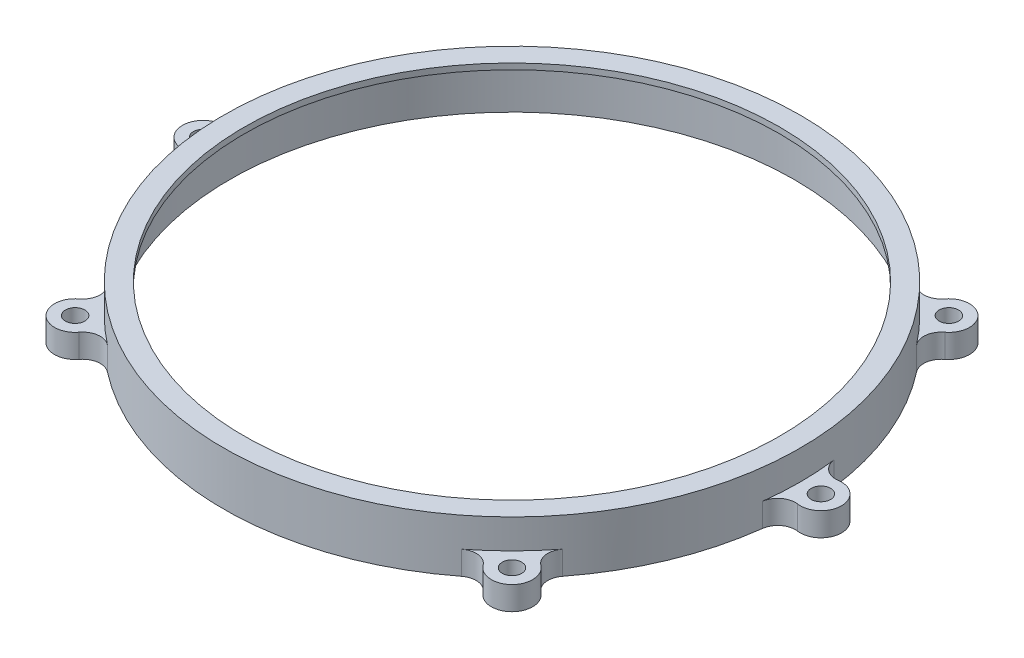
SolidWorks part; units mm, degrees
material "6061 合金"
ref_plane "前视基准面" through (0, 0, 0) normal (0, 0, 1) x (1, 0, 0)
ref_plane "上视基准面" through (0, 0, 0) normal (0, 1, 0) x (1, 0, 0)
ref_plane "右视基准面" through (0, 0, 0) normal (1, 0, 0) x (0, 0, -1)
sketch "草图1" plane through (0, 0, 0) normal (0, 0, 1) x (1, 0, 0)
  line L0 (0, 0) -> (0, 9.3558) construction
  line L1 (48, 8) -> (48, 0)
  line L2 (48, 0) -> (56, 0)
  line L4 (56, 4) -> (49, 4)
  line L5 (49, 4) -> (49, 9)
  line L8 (49, 9) -> (45.5, 9)
  line L9 (45.5, 9) -> (45.5, 8)
  line L10 (45.5, 8) -> (48, 8)
  line L12 (56, 4) -> (56, 0)
  dimension "D1" = 96
  dimension "D2" = 8
  dimension "D3" = 1
  dimension "D4" = 7
  dimension "D5" = 91
  dimension "D6" = 4
  dimension "D8" = 1
revolve "旋转1" add sketch "草图1" angle 360 about L0
hole_wizard "M4 螺纹孔1" positions "草图4" profile "草图3" tap size "M4" standard "GB" end condition through all
sketch "草图4" plane through (0, 0, 0) normal (0, -1, 0) x (-1, 0, 0)
  circle A0 centre (0, 0) radius 52.5 construction
  circle A1 centre (0, 0) radius 56 construction
  point P0 (0, 52.5)
  point P14 (37.1231, 37.1231)
  point P15 (52.5, 0)
  point P16 (37.1231, -37.1231)
  point P17 (0, -52.5)
  point P18 (-37.1231, -37.1231)
  point P19 (-52.5, 0)
  point P20 (-37.1231, 37.1231)
  dimension "D1" = 3.5
  dimension "D2" = 8
cosmetic thread "孔螺蚊线1" parameters "D2"=4
cosmetic thread "孔螺蚊线2" parameters "D2"=4
cosmetic thread "孔螺蚊线3" parameters "D2"=4
cosmetic thread "孔螺蚊线4" parameters "D2"=4
sketch "草图3" plane through (0, 0, -52.5) normal (1, 0, 0) x (0, 0, -1)
  line L0 (0, 0) -> (0, 9)
  line L1 (0, 9) -> (1.65, 9)
  line L2 (1.65, 9) -> (1.65, 0)
  line L5 (1.65, 0) -> (0, 0)
  line L11 (0, -6.35) -> (0, 107.95) construction
  dimension "通孔螺纹孔钻头直径" = 3.3
  dimension "通孔螺纹孔钻头深度" = 9
cosmetic thread "孔螺蚊线5" parameters "D2"=4
cosmetic thread "孔螺蚊线6" parameters "D2"=4
cosmetic thread "孔螺蚊线7" parameters "D2"=4
cosmetic thread "孔螺蚊线8" parameters "D2"=4
sketch "草图5" plane through (0, 0, 0) normal (0, 1, 0) x (1, 0, 0)
  line L0 (-4.95, 0) -> (4.95, 0) construction
  arc A0 (-34.3294, 39.2315) -> (-39.2315, 34.3294) centre (-37.1231, 37.1231) ccw
  circle A1 centre (0, 0) radius 56 construction
  arc A2 (-38.671, 30.0924) -> (-48.6231, 6.066) centre (0, 0) ccw
  arc A3 (34.3294, -39.2315) -> (39.2315, -34.3294) centre (37.1231, -37.1231) ccw
  arc A4 (-38.671, 30.0924) -> (-39.2315, 34.3294) centre (-41.0386, 31.9348) ccw
  arc A5 (-30.0924, 38.671) -> (-34.3294, 39.2315) centre (-31.9348, 41.0386) cw
  arc A6 (3.4663, 52.0154) -> (-3.4663, 52.0154) centre (0, 52.5) ccw construction
  arc A7 (-6.066, 48.6231) -> (-30.0924, 38.671) centre (0, 0) ccw
  arc A8 (-6.066, 48.6231) -> (-3.4663, 52.0154) centre (-6.4374, 51.6) ccw construction
  arc A9 (6.066, 48.6231) -> (3.4663, 52.0154) centre (6.4374, 51.6) cw construction
  arc A10 (39.2315, 34.3294) -> (34.3294, 39.2315) centre (37.1231, 37.1231) ccw
  arc A11 (30.0924, 38.671) -> (6.066, 48.6231) centre (0, 0) ccw
  arc A12 (30.0924, 38.671) -> (34.3294, 39.2315) centre (31.9348, 41.0386) ccw
  arc A13 (38.671, 30.0924) -> (39.2315, 34.3294) centre (41.0386, 31.9348) cw
  arc A14 (52.0154, -3.4663) -> (52.0154, 3.4663) centre (52.5, 0) ccw
  arc A15 (48.6231, 6.066) -> (38.671, 30.0924) centre (0, 0) ccw
  arc A16 (48.6231, 6.066) -> (52.0154, 3.4663) centre (51.6, 6.4374) ccw
  arc A17 (48.6231, -6.066) -> (52.0154, -3.4663) centre (51.6, -6.4374) cw
  circle A18 centre (0, 0) radius 49 construction
  arc A19 (38.671, -30.0924) -> (48.6231, -6.066) centre (0, 0) ccw
  arc A20 (38.671, -30.0924) -> (39.2315, -34.3294) centre (41.0386, -31.9348) ccw
  arc A21 (30.0924, -38.671) -> (34.3294, -39.2315) centre (31.9348, -41.0386) cw
  arc A22 (-3.4663, -52.0154) -> (3.4663, -52.0154) centre (0, -52.5) ccw construction
  arc A23 (6.066, -48.6231) -> (30.0924, -38.671) centre (0, 0) ccw
  arc A24 (6.066, -48.6231) -> (3.4663, -52.0154) centre (6.4374, -51.6) ccw construction
  arc A25 (-6.066, -48.6231) -> (-3.4663, -52.0154) centre (-6.4374, -51.6) cw construction
  arc A26 (-39.2315, -34.3294) -> (-34.3294, -39.2315) centre (-37.1231, -37.1231) ccw
  arc A27 (-30.0924, -38.671) -> (-6.066, -48.6231) centre (0, 0) ccw
  arc A28 (-30.0924, -38.671) -> (-34.3294, -39.2315) centre (-31.9348, -41.0386) ccw
  arc A29 (-38.671, -30.0924) -> (-39.2315, -34.3294) centre (-41.0386, -31.9348) cw
  arc A30 (-52.0154, 3.4663) -> (-52.0154, -3.4663) centre (-52.5, 0) ccw
  arc A31 (-48.6231, -6.066) -> (-38.671, -30.0924) centre (0, 0) ccw
  arc A32 (-48.6231, -6.066) -> (-52.0154, -3.4663) centre (-51.6, -6.4374) ccw
  arc A33 (-48.6231, 6.066) -> (-52.0154, 3.4663) centre (-51.6, 6.4374) cw
  arc A34 (-6.066, 48.6231) -> (6.066, 48.6231) centre (0, 0) cw
  arc A35 (-6.066, -48.6231) -> (6.066, -48.6231) centre (0, 0) ccw
  dimension "D1" = 3
  dimension "D2" = 8
extrude "切除-拉伸1" cut sketch "草图5" along normal through all flip side to cut
